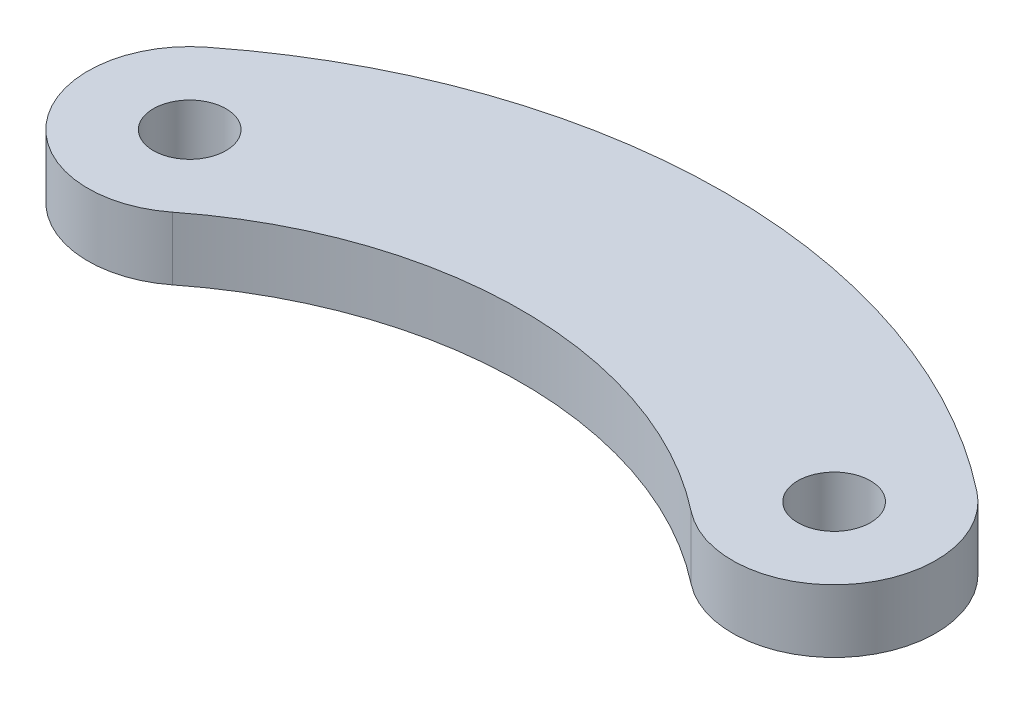
SolidWorks part; units mm, degrees
ref_plane "Alzado" through (0, 0, 0) normal (0, 0, 1) x (1, 0, 0)
ref_plane "Planta" through (0, 0, 0) normal (0, 1, 0) x (1, 0, 0)
ref_plane "Vista lateral" through (0, 0, 0) normal (1, 0, 0) x (0, 0, -1)
sketch "Croquis1" plane through (0, 0, 0) normal (0, 1, 0) x (1, 0, 0)
  line L0 (15.8949, 25.7272) -> (-15.8949, 25.7272) construction
  line L1 (17.5, 25.7272) -> (17.5, 16.9272) construction
  line L2 (-17.5, 25.7272) -> (-17.5, 16.9272) construction
  line L3 (17.5, 12.7272) -> (-17.5, 12.7272) construction
  arc A0 (10.7051, 13.6246) -> (-10.7051, 13.6246) centre (0, 0) ccw
  arc A1 (15.8949, 20.2297) -> (-15.8949, 20.2297) centre (0, 0) ccw
  arc A2 (10.7051, 13.6246) -> (15.8949, 20.2297) centre (13.3, 16.9272) ccw
  arc A3 (-15.8949, 20.2297) -> (-10.7051, 13.6246) centre (-13.3, 16.9272) ccw
  circle A4 centre (13.3, 16.9272) radius 1.5
  circle A5 centre (-13.3, 16.9272) radius 1.5
  dimension "D1" = 8.4
  dimension "D4" = 3
  dimension "D2" = 35
  dimension "D3" = 13
extrude "Saliente-Extruir1" add sketch "Croquis1" along normal blind 2.6
